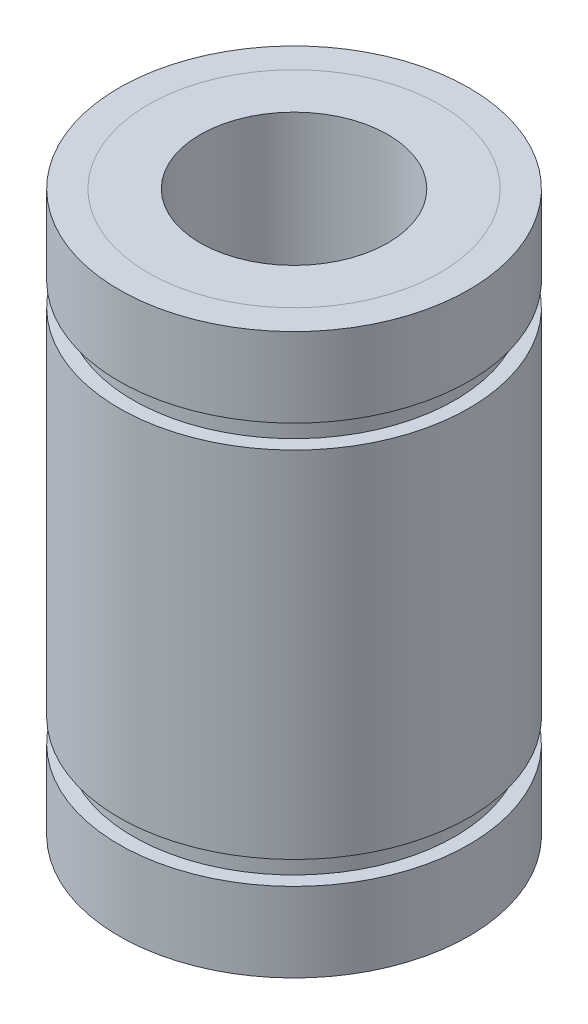
SolidWorks part; units mm, degrees
ref_plane "Alzado" through (0, 0, 0) normal (0, 0, 1) x (1, 0, 0)
ref_plane "Planta" through (0, 0, 0) normal (0, 1, 0) x (1, 0, 0)
ref_plane "Vista lateral" through (0, 0, 0) normal (1, 0, 0) x (0, 0, -1)
sketch "Croquis1" plane through (0, 0, 0) normal (0, 0, 1) x (1, 0, 0)
  line L0 (0, -12) -> (0, 12)
  line L1 (0, 12) -> (7.5, 12)
  line L2 (0, 0) -> (8.6112, 0) construction
  line L3 (7.5, 12) -> (7.5, 8.6)
  line L4 (7.5, 8.6) -> (6.9, 8.6)
  line L5 (6.9, 8.6) -> (6.9, 7.6)
  line L6 (6.9, 7.6) -> (7.5, 7.6)
  line L7 (6.9, -7.6) -> (7.5, -7.6)
  line L8 (6.9, -8.6) -> (6.9, -7.6)
  line L9 (7.5, -8.6) -> (6.9, -8.6)
  line L10 (0, -12) -> (7.5, -12)
  line L11 (7.5, 7.6) -> (7.5, -7.6)
  line L12 (7.5, -8.6) -> (7.5, -12)
  point P16 (7.5, 0)
  dimension "D1" = 12
  dimension "D2" = 7.5
  dimension "D3" = 3.4
  dimension "D4" = 1
  dimension "D5" = 0.6
revolve "Revolución2" add sketch "Croquis1" angle 360 about L0
sketch "Croquis2" plane through (0, 12, 0) normal (0, 1, 0) x (1, 0, 0)
  circle A0 centre (0, 0) radius 6.25
  circle A1 centre (0, 0) radius 7.5 construction
  dimension "D1" = 1.25
extrude "Cortar-Extruir1" cut sketch "Croquis2" against normal through all
sketch "Croquis3" plane through (0, 12, 0) normal (0, 1, 0) x (1, 0, 0)
  circle A1 centre (0, 0) radius 6.25
  circle A2 centre (0, 0) radius 6.25 construction
  circle A3 centre (0, 0) radius 4.025
  dimension "D1" = 8.05
extrude "Saliente-Extruir1" add sketch "Croquis3" against normal blind 24 separate body
